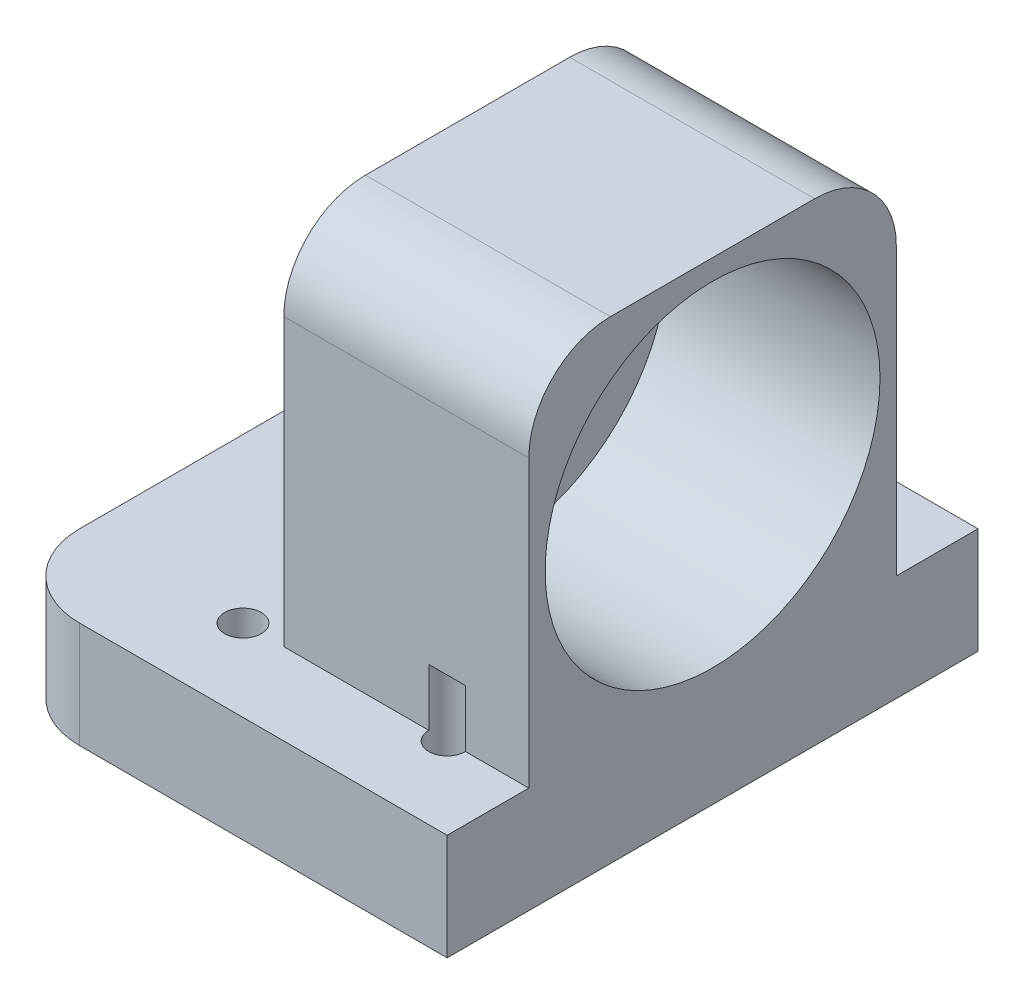
SolidWorks part; units mm, degrees
ref_plane "Front Plane" through (0, 0, 0) normal (0, 0, 1) x (1, 0, 0)
ref_plane "Top Plane" through (0, 0, 0) normal (0, 1, 0) x (1, 0, 0)
ref_plane "Right Plane" through (0, 0, 0) normal (1, 0, 0) x (0, 0, -1)
sketch "Sketch1" plane through (0, 0, 0) normal (0, 1, 0) x (1, 0, 0)
  line L1 (-32.5, 32.5) -> (22.5, 32.5)
  line L2 (-32.5, 32.5) -> (-32.5, -32.5)
  line L3 (-32.5, -32.5) -> (22.5, -32.5)
  line L4 (22.5, 32.5) -> (22.5, -32.5)
  dimension "D1" = 55
  dimension "D2" = 65
  dimension "D3" = 32.5
  dimension "D4" = 22.5
extrude "Boss-Extrude1" add sketch "Sketch1" along normal blind 13
sketch "Sketch2" plane through (0, 13, 0) normal (0, 1, 0) x (1, 0, 0)
  line L0 (22.5, -32.5) -> (22.5, 32.5) construction
  line L1 (22.5, 22.5) -> (-7.5, 22.5)
  line L2 (22.5, 22.5) -> (22.5, -22.5)
  line L3 (22.5, -22.5) -> (-7.5, -22.5)
  line L4 (-7.5, 22.5) -> (-7.5, -22.5)
  dimension "D1" = 45
  dimension "D2" = 22.5
  dimension "D3" = 30
extrude "Boss-Extrude2" add sketch "Sketch2" along normal blind 50
sketch "Sketch5" plane through (22.5, 0, 0) normal (1, 0, 0) x (0, 0, -1)
  circle A0 centre (0, 35) radius 20.5
  dimension "D1" = 41
  dimension "D2" = 35
extrude "Cut-Extrude1" cut sketch "Sketch5" against normal blind 26
sketch "Sketch7" plane through (-3.5, 0, 0) normal (1, 0, 0) x (0, 0, -1)
  circle A0 centre (0, 35) radius 7
  dimension "D1" = 14
  dimension "D2" = 35
extrude "Cut-Extrude2" cut sketch "Sketch7" against normal blind 20
sketch "Sketch8" plane through (0, 0, 0) normal (0, -1, 0) x (-1, 0, 0)
  line L0 (32.5, 32.5) -> (32.5, -32.5) construction
  circle A0 centre (12.5, -22.5) radius 2.25
  circle A1 centre (12.5, 22.5) radius 2.25
  circle A2 centre (-12.5, 22.5) radius 2.25
  circle A3 centre (-12.5, -22.5) radius 2.25
  dimension "D1" = 4.5
  dimension "D2" = 4.5
  dimension "D3" = 4.5
  dimension "D4" = 4.5
  dimension "D5" = 25
  dimension "D6" = 22.5
  dimension "D7" = 22.5
  dimension "D8" = 22.5
  dimension "D9" = 22.5
  dimension "D10" = 20
  dimension "D11" = 20
  dimension "D12" = 25
extrude "Cut-Extrude3" cut sketch "Sketch8" against normal blind 20
fillet "Fillet2" radius 10 1 edges at (-32.5, 6.5, 32.5)
sketch "Sketch9" plane through (0, 63, 0) normal (0, 1, 0) x (1, 0, 0)
  line L1 (-7.5, 22.5) -> (22.5, 22.5)
  line L2 (-7.5, 22.5) -> (-7.5, -22.5)
  line L3 (-7.5, -22.5) -> (22.5, -22.5)
  line L4 (22.5, 22.5) -> (22.5, -22.5)
extrude "Cut-Extrude4" cut sketch "Sketch9" against normal blind 5
fillet "Fillet3" radius 10 1 edges at (7.5, 58, 22.5)
fillet "Fillet4" radius 10 1 edges at (7.5, 58, -22.5)
